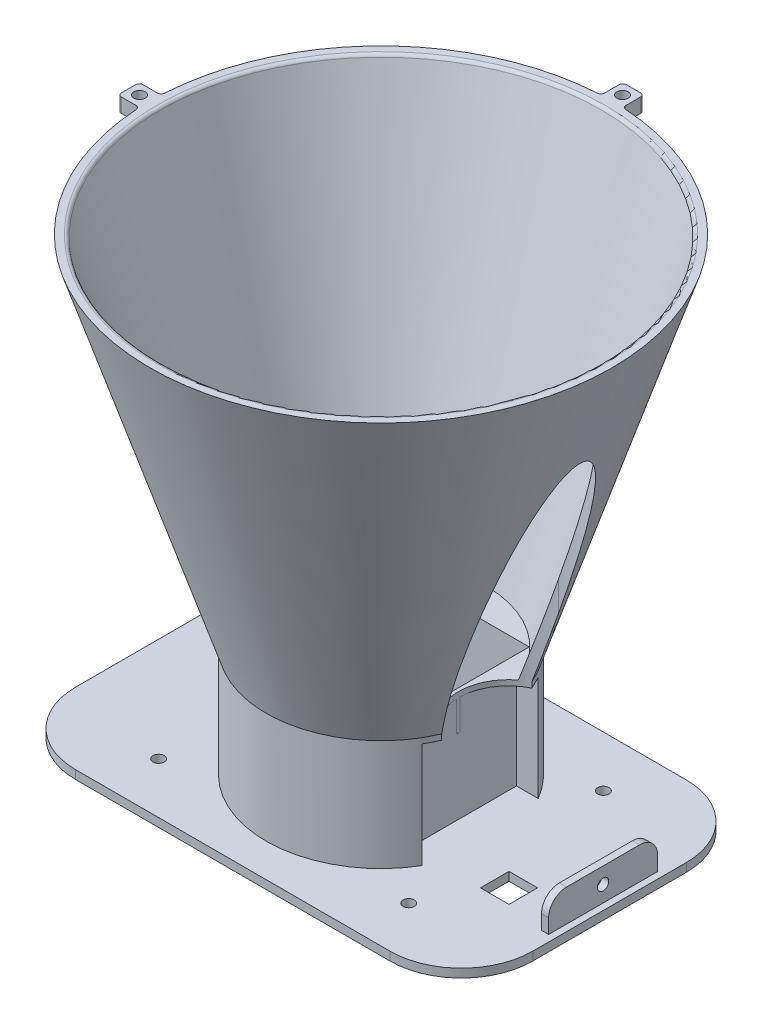
SolidWorks part; units mm, degrees
ref_plane "Front Plane" through (0, 0, 0) normal (0, 0, 1) x (1, 0, 0)
ref_plane "Top Plane" through (0, 0, 0) normal (0, 1, 0) x (1, 0, 0)
ref_plane "Right Plane" through (0, 0, 0) normal (1, 0, 0) x (0, 0, -1)
sketch "Sketch2" plane through (0, 0, 0) normal (0, 1, 0) x (1, 0, 0)
  line L1 (0, 0) -> (128, 0)
  line L2 (0, 0) -> (0, 83)
  line L3 (0, 83) -> (128, 83)
  line L4 (128, 0) -> (128, 83)
  dimension "D1" = 128
  dimension "D2" = 83
extrude "Boss-Extrude1" add sketch "Sketch2" along normal blind 2.4
sketch "Sketch3" plane through (0, 2.4, 0) normal (0, 1, 0) x (1, 0, 0)
  line L0 (64, 83) -> (64, 50083) construction
  line L1 (29, 68.75) -> (99, 68.75) construction
  line L2 (29, 68.75) -> (29, 14.25) construction
  line L3 (29, 14.25) -> (99, 14.25) construction
  line L4 (99, 68.75) -> (99, 14.25) construction
  line L5 (128, 83) -> (0, 83) construction
  line L6 (0, 41.5) -> (-50000, 41.5) construction
  line L7 (0, 83) -> (0, 0) construction
  point P8 (64, 83)
  point P13 (0, 41.5)
  point P14 (64, 68.75)
  point P15 (29, 41.5)
  point P17 (29, 68.75)
  point P18 (29, 14.25)
  point P19 (99, 14.25)
  point P20 (99, 68.75)
  dimension "D1" = 70
  dimension "D2" = 54.5
sketch "Sketch4" plane through (0, 2.4, 0) normal (0, 1, 0) x (1, 0, 0)
  circle A0 centre (29, 68.75) radius 1.575
  circle A1 centre (99, 68.75) radius 1.575
  circle A2 centre (29, 14.25) radius 1.575
  circle A3 centre (99, 14.25) radius 1.575
  dimension "D1" = 3.15
  dimension "D2" = 3.15
  dimension "D3" = 3.15
  dimension "D4" = 3.15
extrude "Cut-Extrude1" cut sketch "Sketch4" against normal through all
sketch "Sketch5" plane through (0, 2.4, 0) normal (0, 1, 0) x (1, 0, 0)
  line L0 (64, -199917) -> (64, 250083) construction
  line L1 (47.5, 25) -> (80.5, 25) construction
  line L2 (47.5, 25) -> (47.5, 58) construction
  line L3 (47.5, 58) -> (80.5, 58) construction
  line L4 (80.5, 25) -> (80.5, 58) construction
  line L5 (200000, 41.5) -> (-250000, 41.5) construction
  circle A0 centre (47.5, 58) radius 1.85
  circle A1 centre (80.5, 58) radius 1.85
  circle A2 centre (47.5, 25) radius 1.85
  circle A3 centre (80.5, 25) radius 1.85
  point P4 (64, 58)
  point P7 (47.5, 41.5)
  point P11 (47.5, 58)
  point P12 (47.5, 25)
  point P13 (80.5, 25)
  point P14 (80.5, 58)
  dimension "D3" = 3.7
  dimension "D4" = 3.7
  dimension "D5" = 3.7
  dimension "D6" = 3.7
  dimension "D1" = 33
  dimension "D2" = 33
extrude "Cut-Extrude2" cut sketch "Sketch5" against normal through all
sketch "Sketch6" plane through (0, 2.4, 0) normal (0, 1, 0) x (1, 0, 0)
  line L0 (64, 83) -> (64, 50083) construction
  line L1 (128, 83) -> (0, 83) construction
  line L2 (0, 41.5) -> (50000, 41.5) construction
  line L3 (0, 83) -> (0, 0) construction
  line L5 (41.25, 18.75) -> (86.75, 18.75) construction
  line L6 (41.25, 18.75) -> (41.25, 64.25) construction
  line L7 (41.25, 64.25) -> (86.75, 64.25) construction
  line L8 (86.75, 18.75) -> (86.75, 64.25) construction
  line L9 (41.25, 18.75) -> (86.75, 64.25) construction
  line L10 (41.25, 64.25) -> (86.75, 18.75) construction
  circle A0 centre (64, 41.5) radius 32.1734
  point P4 (64, 83)
  point P9 (0, 41.5)
  point P10 (64, 41.5)
  dimension "D1" = 45.5
  dimension "D2" = 45.5
extrude "Boss-Extrude2" add sketch "Sketch6" along normal blind 31
sketch "Sketch7" plane through (0, 2.4, 0) normal (0, 1, 0) x (1, 0, 0)
  line L5 (43.25, 20.75) -> (84.75, 20.75)
  line L6 (43.25, 20.75) -> (43.25, 62.25)
  line L7 (43.25, 62.25) -> (84.75, 62.25)
  line L8 (84.75, 20.75) -> (84.75, 62.25)
  line L9 (43.25, 20.75) -> (84.75, 62.25) construction
  line L10 (43.25, 62.25) -> (84.75, 20.75) construction
  point P0 (64, 41.5)
  dimension "D1" = 41.5
  dimension "D2" = 41.5
extrude "Cut-Extrude5" cut sketch "Sketch7" along normal through all
ref_plane "Plane4" through (0, 0, -41.5) normal (0, 0, 1) x (1, 0, 0)
sketch "Sketch8" plane through (0, 0, -41.5) normal (0, 0, 1) x (1, 0, 0)
  line L0 (96.1734, 33.4) -> (96.1734, 133.4) construction
  line L1 (96.1734, 33.4) -> (128.6653, 133.4)
  line L2 (96.1734, 33.4) -> (93.4734, 33.4)
  line L3 (96.1734, 33.4) -> (31.8266, 33.4) construction
  line L4 (93.4734, 33.4) -> (125.9653, 133.4)
  line L5 (125.9653, 133.4) -> (128.6653, 133.4)
  line L6 (64, 33.4) -> (64, 54.7105) construction
  dimension "D1" = 100
  dimension "D2" = 18
  dimension "D3" = 2.7
revolve "Revolve1" add sketch "Sketch8" angle 360 about L6
sketch "Sketch9" plane through (0, 133.4, 0) normal (0, 1, 0) x (1, 0, 0)
  line L0 (64, 62.25) -> (64, 50062.25) construction
  line L1 (84.75, 62.25) -> (43.25, 62.25) construction
  line L2 (43.25, 41.5) -> (50043.25, 41.5) construction
  line L3 (43.25, 62.25) -> (43.25, 20.75) construction
  line L4 (61, 106.1653) -> (67, 106.1653)
  line L5 (67, 106.1653) -> (67, 112.1653)
  line L6 (67, 112.1653) -> (61, 112.1653)
  line L7 (61, 112.1653) -> (61, 106.1653)
  line L8 (64, 41.5) -> (-35125.5638, 35231.0638) construction
  line L9 (-6.6653, 38.5) -> (-6.6653, 44.5)
  line L10 (-0.6653, 38.5) -> (-6.6653, 38.5)
  line L11 (-0.6653, 44.5) -> (-0.6653, 38.5)
  line L12 (-6.6653, 44.5) -> (-0.6653, 44.5)
  circle A1 centre (64, 41.5) radius 64.6653 construction
  point P4 (64, 62.25)
  point P9 (43.25, 41.5)
  point P13 (64, 106.1653)
  dimension "D1" = 6
  dimension "D2" = 6
  dimension "D3" = 45
extrude "Boss-Extrude3" add sketch "Sketch9" against normal blind 4 separate body
sketch "Sketch10" plane through (-0.6653, 0, 0) normal (1, 0, 0) x (0, 0, -1)
  line L1 (38.5, 129.4) -> (44.5, 129.4)
  line L2 (38.5, 129.4) -> (38.5, 133.4)
  line L3 (38.5, 133.4) -> (44.5, 133.4)
  line L4 (44.5, 129.4) -> (44.5, 133.4)
extrude "Boss-Extrude4" add sketch "Sketch10" along normal up to next
sketch "Sketch11" plane through (0, 0, -106.1653) normal (0, 0, 1) x (1, 0, 0)
  line L1 (67, 133.4) -> (61, 133.4)
  line L2 (67, 133.4) -> (67, 129.4)
  line L3 (67, 129.4) -> (61, 129.4)
  line L4 (61, 133.4) -> (61, 129.4)
extrude "Boss-Extrude5" add sketch "Sketch11" along normal up to next
sketch "Sketch12" plane through (0, 133.4, 0) normal (0, 1, 0) x (1, 0, 0)
  line L0 (61, 106.0957) -> (61, 112.1653) construction
  line L1 (61, 112.1653) -> (67, 112.1653) construction
  line L2 (43.25, 41.5) -> (50043.25, 41.5) construction
  line L3 (43.25, 62.25) -> (43.25, 20.75) construction
  line L4 (64, 62.25) -> (64, -49937.75) construction
  line L5 (84.75, 62.25) -> (43.25, 62.25) construction
  line L6 (64, 41.5) -> (59.6229, 45.8771) construction
  circle A0 centre (64, 109.1305) radius 1.575
  circle A1 centre (-3.6305, 41.5) radius 1.575
  point P6 (64, 112.1653)
  point P9 (61, 109.1305)
  point P14 (43.25, 41.5)
  point P19 (64, 62.25)
  point P20 (64, 41.5)
  dimension "D1" = 3.15
  dimension "D2" = 45
extrude "Cut-Extrude6" cut sketch "Sketch12" against normal through all
sketch "Sketch13" plane through (128, 0, 0) normal (1, 0, 0) x (0, 0, -1)
  line L0 (0, 0) -> (83, 0) construction
  line L1 (0, 2.4) -> (0, 0) construction
  line L2 (0, 2.4) -> (83, 2.4) construction
  line L3 (26.25, 0) -> (56.75, 0)
  line L4 (26.25, 0) -> (26.25, 2.4)
  line L5 (26.25, 2.4) -> (56.75, 2.4)
  line L6 (56.75, 0) -> (56.75, 2.4)
  point P0 (26.25, 0)
  dimension "D1" = 26.25
  dimension "D2" = 30.5
extrude "Boss-Extrude6" add sketch "Sketch13" along normal blind 4.5
sketch "Sketch14" plane through (0, 2.4, 0) normal (0, 1, 0) x (1, 0, 0)
  line L0 (132.5, 26.25) -> (128, 26.25) construction
  line L1 (132.5, 56.75) -> (124.18, 56.75)
  line L2 (132.5, 56.75) -> (132.5, 26.25)
  line L3 (132.5, 26.25) -> (124.18, 26.25)
  line L4 (124.18, 56.75) -> (124.18, 26.25)
  dimension "D1" = 8.32
extrude "Boss-Extrude7" add sketch "Sketch14" along normal blind 9
sketch "Sketch15" plane through (132.5, 0, 0) normal (1, 0, 0) x (0, 0, -1)
  line L0 (26.25, 11.4) -> (56.75, 11.4) construction
  line L1 (26.25, 11.4) -> (56.75, 11.4) construction
  circle A0 centre (41.5, 6.9) radius 1.575
  point P8 (41.5, 11.4)
  dimension "D1" = 3.15
  dimension "D2" = 4.5
extrude "Cut-Extrude7" cut sketch "Sketch15" against normal blind 9
sketch "Sketch17" plane through (0, 0, 0) normal (0, -1, 0) x (1, 0, 0)
  line L0 (128, 0) -> (113.33, 0) construction
  line L1 (0, 0) -> (128, 0) construction
  line L2 (113.33, 0) -> (113.33, -28) construction
  line L4 (113.33, -28) -> (105.33, -28)
  line L5 (113.33, -28) -> (113.33, -36)
  line L6 (113.33, -36) -> (105.33, -36)
  line L7 (105.33, -28) -> (105.33, -36)
  dimension "D1" = 14.67
  dimension "D2" = 28
  dimension "D3" = 8
  dimension "D4" = 8
extrude "Cut-Extrude9" cut sketch "Sketch17" against normal blind 10
sketch "Sketch18" plane through (0, 0, 0) normal (0, -1, 0) x (1, 0, 0)
  line L0 (80.5, -26.85) -> (80.5, -27.85) construction
  line L1 (77.5, -27.85) -> (83.5, -27.85)
  line L2 (77.5, -27.85) -> (77.5, -37.85)
  line L3 (77.5, -37.85) -> (83.5, -37.85)
  line L4 (83.5, -37.85) -> (83.5, -27.85)
  circle A0 centre (80.5, -25) radius 1.85 construction
  point P7 (80.5, -27.85)
  dimension "D1" = 1
  dimension "D2" = 6
  dimension "D3" = 10
extrude "Cut-Extrude10" cut sketch "Sketch18" against normal blind 10
fillet "Fillet3" radius 20 4 edges at (0, 1.2, -83) (0, 1.2, 0) (128, 1.2, -83) (128, 1.2, 0)
fillet "Fillet4" radius 1 8 edges at (67, 131.4, -112.1653) (61, 131.4, -112.1653) (-6.6653, 131.4, -44.5) (-6.6653, 131.4, -38.5)
fillet "Fillet6" radius 5 2 edges at (128.34, 11.4, -56.75) (128.34, 11.4, -26.25)
fillet "Fillet7" radius 1 1 edges at (64, 133.4, -103.4653)
ref_plane "Plane5" through (96.1734, 0, 0) normal (1, 0, 0) x (0, -1, 0)
sketch "Sketch19" plane through (0, 2.4, 0) normal (0, 1, 0) x (1, 0, 0)
  line L1 (43.25, 62.25) -> (84.75, 62.25)
  line L2 (43.25, 62.25) -> (43.25, 20.75)
  line L3 (43.25, 20.75) -> (84.75, 20.75)
  line L4 (84.75, 62.25) -> (84.75, 20.75)
  line L5 (77.5, 37.85) -> (83.5, 37.85)
  line L6 (77.5, 37.85) -> (77.5, 27.85)
  line L7 (77.5, 27.85) -> (83.5, 27.85)
  line L8 (83.5, 37.85) -> (83.5, 27.85)
  circle A0 centre (80.5, 58) radius 1.575
  circle A1 centre (47.5, 58) radius 1.575
  circle A2 centre (47.5, 25) radius 1.575
  circle A3 centre (80.5, 25) radius 1.575
  dimension "D1" = 3.15
  dimension "D2" = 3.15
  dimension "D3" = 3.15
  dimension "D4" = 3.15
extrude "Boss-Extrude8" add sketch "Sketch19" along normal blind 8
sketch "Sketch20" plane through (0, 0, 0) normal (0, -1, 0) x (1, 0, 0)
  line L1 (84.75, -20.75) -> (43.25, -20.75)
  line L2 (84.75, -20.75) -> (84.75, -62.25)
  line L3 (84.75, -62.25) -> (43.25, -62.25)
  line L4 (43.25, -20.75) -> (43.25, -62.25)
  line L5 (77.5, -27.85) -> (83.5, -27.85)
  line L6 (77.5, -27.85) -> (77.5, -37.85)
  line L7 (77.5, -37.85) -> (83.5, -37.85)
  line L8 (83.5, -27.85) -> (83.5, -37.85)
  circle A0 centre (47.5, -25) radius 1.575
  circle A1 centre (80.5, -25) radius 1.575
  circle A2 centre (80.5, -58) radius 1.575
  circle A3 centre (47.5, -58) radius 1.575
  dimension "D1" = 3.15
  dimension "D2" = 3.15
  dimension "D3" = 3.15
  dimension "D4" = 3.15
extrude "Cut-Extrude11" cut sketch "Sketch20" against normal blind 5.5
ref_plane "Plane6" through (96.1734, 0, 0) normal (1, 0, 0) x (0, -1, 0)
sketch "Sketch22" plane through (96.1734, 0, 0) normal (1, 0, 0) x (0, -1, 0)
  line L0 (-2.4, 57.75) -> (-31.9, 57.75)
  line L1 (-2.4, 73.6734) -> (-2.4, 9.3266) construction
  line L2 (0, 56.75) -> (-6.4, 56.75) construction
  line L3 (-2.4, 25.25) -> (-31.9, 25.25)
  line L4 (-2.4, 20) -> (-2.4, 26.25) construction
  line L5 (-6.4, 26.25) -> (0, 26.25) construction
  line L6 (-31.9, 57.75) -> (-31.9, 25.25)
  line L7 (-2.4, 57.75) -> (-2.4, 25.25)
  dimension "D1" = 29.5
  dimension "D2" = 1
  dimension "D3" = 1
extrude "Cut-Extrude12" cut sketch "Sketch22" against normal blind 10.5
sketch "Sketch24" plane through (0, 0, -26.25) normal (0, 0, 1) x (1, 0, 0)
  line L0 (132.5, 6.4) -> (132.5, 0) construction
  line L1 (128, 2.4) -> (126.18, 2.4)
  line L2 (132.5, 2.4) -> (132.5, 12.9673)
  line L3 (132.5, 12.9673) -> (126.18, 12.9673)
  line L4 (126.18, 2.4) -> (126.18, 12.9673)
  line L7 (128, 2.4) -> (128, 0)
  line L8 (128, 0) -> (132.5, 0)
  line L9 (132.5, 2.4) -> (132.5, 0)
  dimension "D1" = 6.32
extrude "Cut-Extrude13" cut sketch "Sketch24" against normal through all
sketch "Sketch25" plane through (0, 133.4, 0) normal (0, 1, 0) x (1, 0, 0)
  line L0 (128.6653, 41.5) -> (99.6653, 41.5) construction
  arc A0 (-0.5451, 37.558) -> (67.942, 106.0451) centre (64, 41.5) ccw construction
  arc A1 (99.6653, 55.5) -> (99.6653, 27.5) centre (99.6653, 41.5) ccw
  ellipse E0 centre (99.6653, 41.5) end of major axis (79.6653, 41.5) minor radius 14 (99.6653, 27.5) -> (99.6653, 55.5) ccw
  dimension "D2" = 28
  dimension "D1" = 29
  dimension "D3" = 20
extrude "Cut-Extrude14" cut sketch "Sketch25" against normal blind 110
